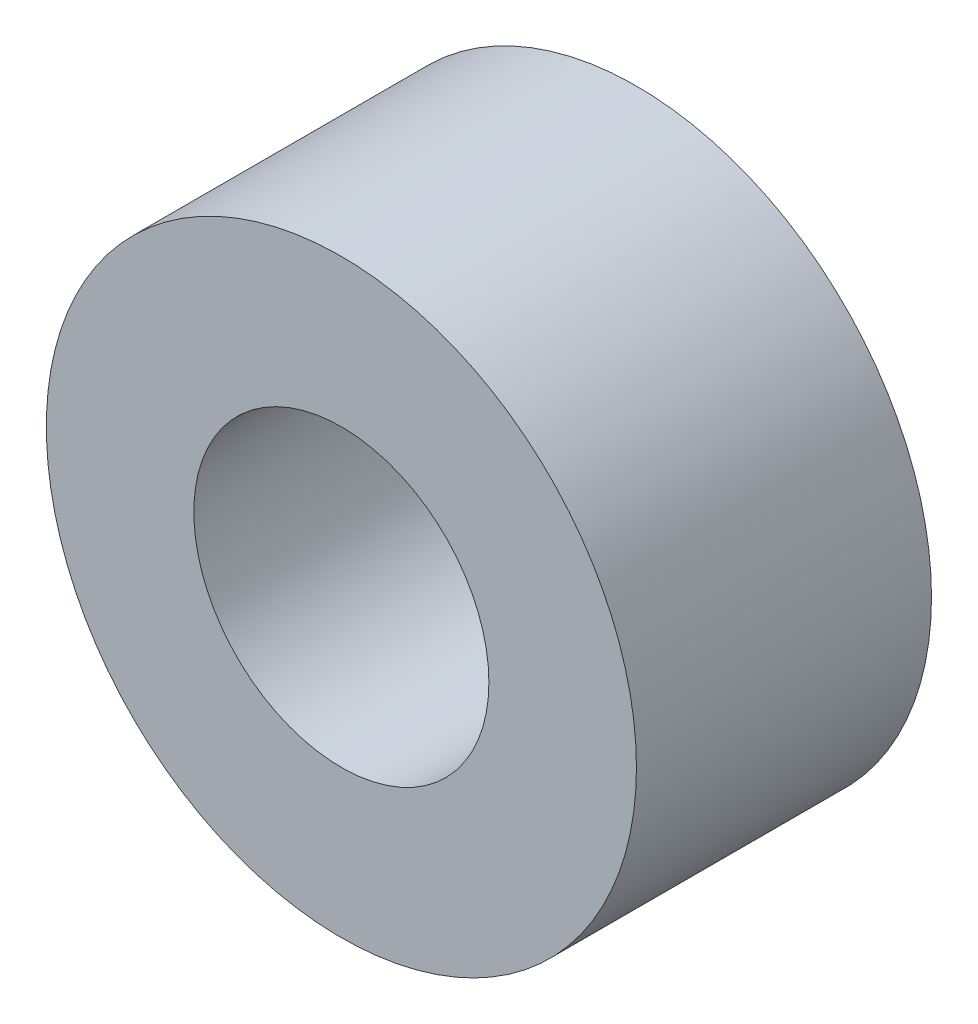
SolidWorks part; units mm, degrees
material "Birch Plywood"
ref_plane "Front Plane" through (0, 0, 0) normal (0, 0, 1) x (1, 0, 0)
ref_plane "Top Plane" through (0, 0, 0) normal (0, 1, 0) x (1, 0, 0)
ref_plane "Right Plane" through (0, 0, 0) normal (1, 0, 0) x (0, 0, -1)
sketch "Sketch1" plane through (0, 0, 0) normal (0, 0, 1) x (1, 0, 0)
  circle A0 centre (0, 0) radius 6.35
  circle A1 centre (0, 0) radius 3.175
  dimension "D1" = 6.35
  dimension "D2" = 12.7
extrude "Boss-Extrude1" add sketch "Sketch1" along normal blind 6.35
